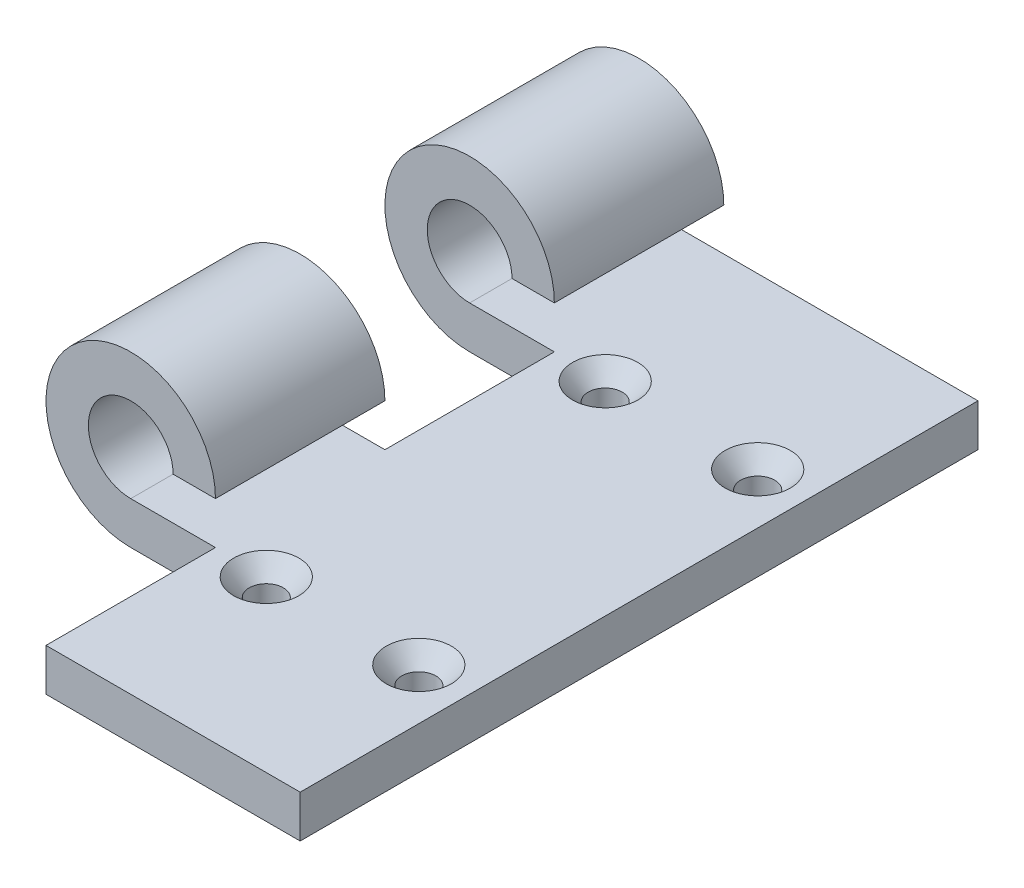
SolidWorks part; units mm, degrees
ref_plane "Front Plane" through (0, 0, 0) normal (0, 0, 1) x (1, 0, 0)
ref_plane "Top Plane" through (0, 0, 0) normal (0, 1, 0) x (1, 0, 0)
ref_plane "Right Plane" through (0, 0, 0) normal (1, 0, 0) x (0, 0, -1)
sketch "Sketch1" plane through (0, 0, 0) normal (0, 0, 1) x (1, 0, 0)
  line L0 (0, -12.7) -> (50.8, -12.7)
  arc A0 (0, -12.7) -> (12.7, 0) centre (0, 0) cw
  point P5 (0, 0)
  point P6 (0, 0)
  dimension "D1" = 12.7
  dimension "D2" = 50.8
extrude "Extrude-Thin1" add sketch "Sketch1" along normal mid plane 101.6 thin thin type one direction wall 6.35
sketch "Sketch3" plane through (0, -6.35, 0) normal (0, 1, 0) x (1, 0, 0)
  line L0 (50.8, -50.8) -> (0, -50.8) construction
  line L1 (-12.7, -25.4) -> (12.7, -25.4)
  line L2 (-12.7, -25.4) -> (-12.7, -50.8)
  line L3 (-12.7, -50.8) -> (12.7, -50.8)
  line L4 (12.7, -25.4) -> (12.7, -50.8)
  line L5 (-12.7, -25.4) -> (12.7, -50.8) construction
  line L6 (-12.7, -50.8) -> (12.7, -25.4) construction
  line L7 (-12.7, -50.8) -> (12.7, -50.8) construction
  point P0 (0, -38.1)
  dimension "D1" = 25.4
  dimension "D2" = 25.4
extrude "Cut-Extrude1" cut sketch "Sketch3" against normal through all both and the other way through all
pattern_linear "LPattern1" count 2 spacing 50.8 along (0, 0, -1) of "Cut-Extrude1"
hole_wizard "CSK for #10 Flat Head Machine Screw1" positions "Sketch6" profile "Sketch7" countersink size "#10" standard "ANSI Inch" end condition through all
sketch "Sketch6" plane through (0, -6.35, 0) normal (0, 1, 0) x (1, 0, 0)
  line L0 (50.8, 50.8) -> (0, 50.8) construction
  line L1 (12.7, 25.4) -> (12.7, 0) construction
  point P0 (20.32, 25.4)
  dimension "D1" = 25.4
  dimension "D2" = 7.62
sketch "Sketch7" plane through (20.32, -6.35, -25.4) normal (1, 0, 0) x (0, 0, 1)
  line L0 (0, 0) -> (0, 6.35)
  line L1 (0, 6.35) -> (2.5527, 6.35)
  line L2 (2.5527, 6.35) -> (2.5527, 2.6882)
  line L3 (2.5527, 2.6882) -> (4.8895, 0)
  line L5 (4.8895, 0) -> (0, 0)
  line L6 (-2.5527, 2.6882) -> (-4.8895, 0) construction
  line L11 (0, -6.35) -> (0, 107.95) construction
  dimension "Thru Hole Dia." = 5.1054
  dimension "Thru Hole Depth" = 6.35
  dimension "Near C'Sink Dia." = 9.779
  dimension "Near C'Sink Angle" = 82
pattern_linear "LPattern2" count 2 spacing 50.8 along (0, 0, 1) count 2 spacing 22.86 along (1, 0, 0) of "CSK for #10 Flat Head Machine Screw1"
